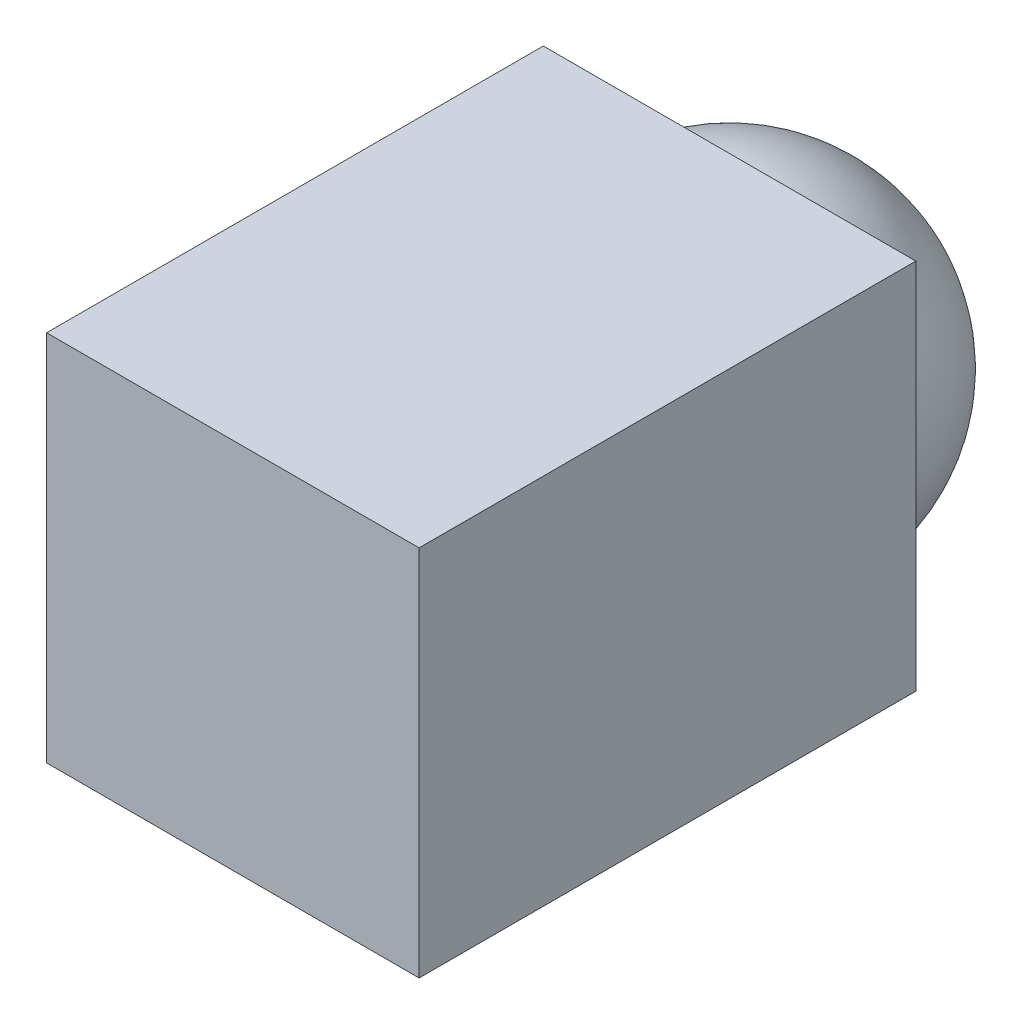
SolidWorks part; units mm, degrees
ref_plane "Front Plane" through (0, 0, 0) normal (0, 0, 1) x (1, 0, 0)
ref_plane "Top Plane" through (0, 0, 0) normal (0, 1, 0) x (1, 0, 0)
ref_plane "Right Plane" through (0, 0, 0) normal (1, 0, 0) x (0, 0, -1)
sketch "Sketch1" plane through (0, 0, 0) normal (0, 0, 1) x (1, 0, 0)
  line L1 (0, 0) -> (15, 0)
  line L2 (0, 0) -> (0, -15)
  line L3 (0, -15) -> (15, -15)
  line L4 (15, 0) -> (15, -15)
extrude "Boss-Extrude1" add sketch "Sketch1" along normal blind 20
sketch "Sketch2" plane through (0, 0, 0) normal (0, 0, -1) x (-1, 0, 0)
  line L0 (-14.5, -7.5) -> (-0.5, -7.5)
  arc A0 (-14.5, -7.5) -> (-0.5, -7.5) centre (-7.5, -7.5) ccw
revolve "Revolve1" add sketch "Sketch2" angle 180 about L0
